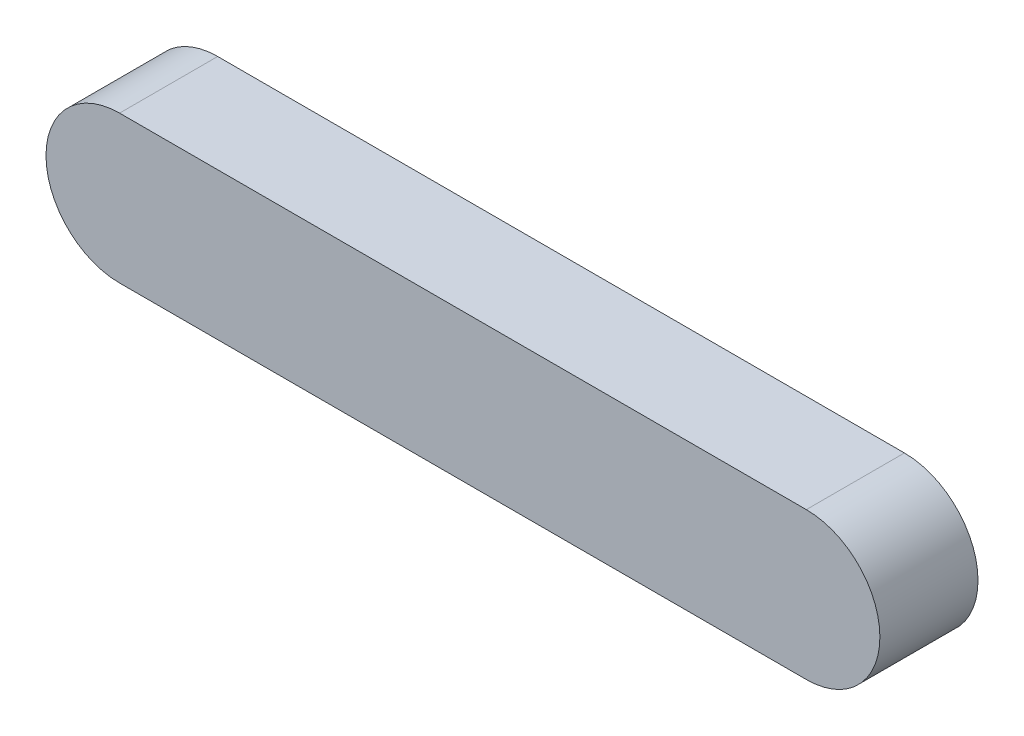
SolidWorks part; units mm, degrees
ref_plane "前视基准面" through (0, 0, 0) normal (0, 0, 1) x (1, 0, 0)
ref_plane "上视基准面" through (0, 0, 0) normal (0, 1, 0) x (1, 0, 0)
ref_plane "右视基准面" through (0, 0, 0) normal (1, 0, 0) x (0, 0, -1)
other "Configuration Table"
sketch "草图1" plane through (0, 0, 0) normal (0, 0, 1) x (1, 0, 0)
  line L0 (70, 0) -> (0, 0) construction
  line L1 (70, -7.5) -> (0, -7.5)
  line L2 (70, 7.5) -> (0, 7.5)
  arc A0 (70, -7.5) -> (70, 7.5) centre (70, 0) ccw
  arc A1 (0, 7.5) -> (0, -7.5) centre (0, 0) ccw
  point P0 (35, 0)
  dimension "D1" = 70
  dimension "D2" = 15
extrude "凸台-拉伸1" add sketch "草图1" along normal blind 10
